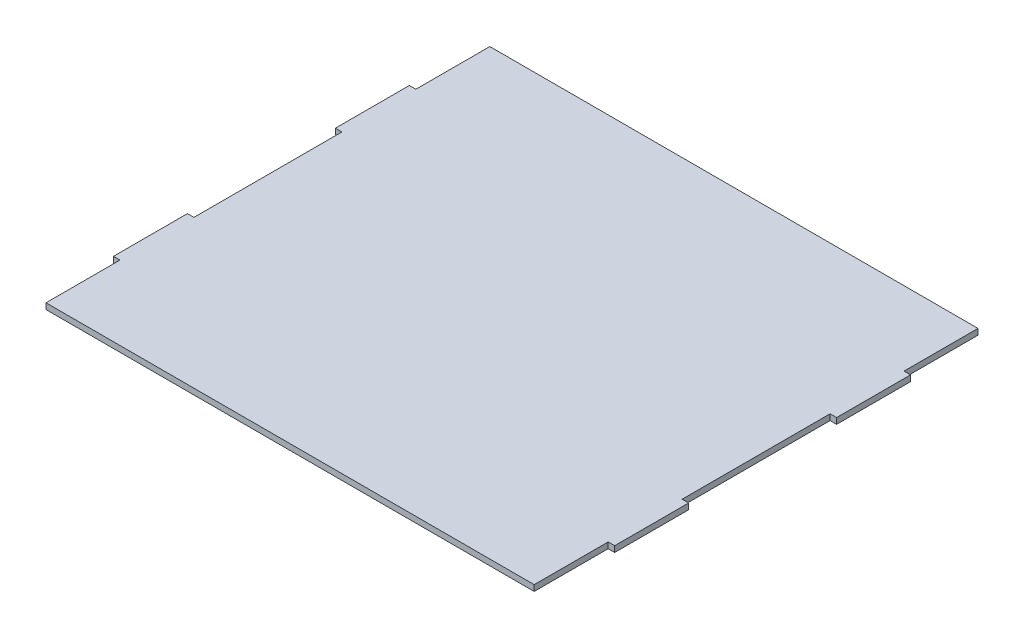
SolidWorks part; units mm, degrees
ref_plane "Front Plane" through (0, 0, 0) normal (0, 0, 1) x (1, 0, 0)
ref_plane "Top Plane" through (0, 0, 0) normal (0, 1, 0) x (1, 0, 0)
ref_plane "Right Plane" through (0, 0, 0) normal (1, 0, 0) x (0, 0, -1)
sketch "Sketch1" plane through (0, 0, 0) normal (0, 1, 0) x (1, 0, 0)
  line L1 (-84.7, 75) -> (84.7, 75)
  line L2 (-84.7, 75) -> (-84.7, -75)
  line L3 (-84.7, -75) -> (84.7, -75)
  line L4 (84.7, 75) -> (84.7, -75)
  line L5 (-84.7, 75) -> (84.7, -75) construction
  line L6 (-84.7, -75) -> (84.7, 75) construction
  point P0 (0, 0)
  dimension "D1" = 169.4
  dimension "D2" = 150
extrude "Boss-Extrude1" add sketch "Sketch1" along normal blind 2
sketch "Sketch2" plane through (0, 2, 0) normal (0, 1, 0) x (1, 0, 0)
  line L1 (82.5, -50) -> (82.5, -75)
  line L4 (-82.5, 50) -> (-82.5, 75)
  line L7 (-87.9231, 75) -> (-87.9231, -75)
  line L14 (-82.5, -50) -> (-84.7, -50)
  line L18 (-82.5, -50) -> (-82.5, -75)
  line L20 (-82.5, -75) -> (-87.9231, -75)
  line L23 (-87.9231, 75) -> (-82.5, 75)
  line L26 (-84.7, 25) -> (-82.5, 25)
  line L27 (-82.5, 25) -> (-82.5, -25)
  line L28 (-82.5, -25) -> (-84.7, -25)
  line L41 (87.9231, -75) -> (87.9231, 75)
  line L43 (82.5, 50) -> (84.7, 50)
  line L44 (-82.5, 50) -> (-84.7, 50)
  line L45 (82.5, 50) -> (82.5, 75)
  line L46 (-84.7, 75) -> (-84.7, -75) construction
  line L47 (-84.7, 50) -> (-84.7, 25)
  line L48 (-84.7, -25) -> (-84.7, -50)
  line L49 (82.5, 75) -> (87.9231, 75)
  line L50 (87.9231, -75) -> (82.5, -75)
  line L51 (84.7, -25) -> (82.5, -25)
  line L52 (82.5, -25) -> (82.5, 25)
  line L53 (82.5, 25) -> (84.7, 25)
  line L54 (82.5, -50) -> (84.7, -50)
  line L55 (84.7, -75) -> (84.7, 75) construction
  line L56 (84.7, -50) -> (84.7, -25)
  line L57 (84.7, 25) -> (84.7, 50)
  dimension "D1" = 25
  dimension "D2" = 2.2
  dimension "D3" = 2.2
  dimension "D4" = 25
extrude "Cut-Extrude1" cut sketch "Sketch2" against normal blind 2
